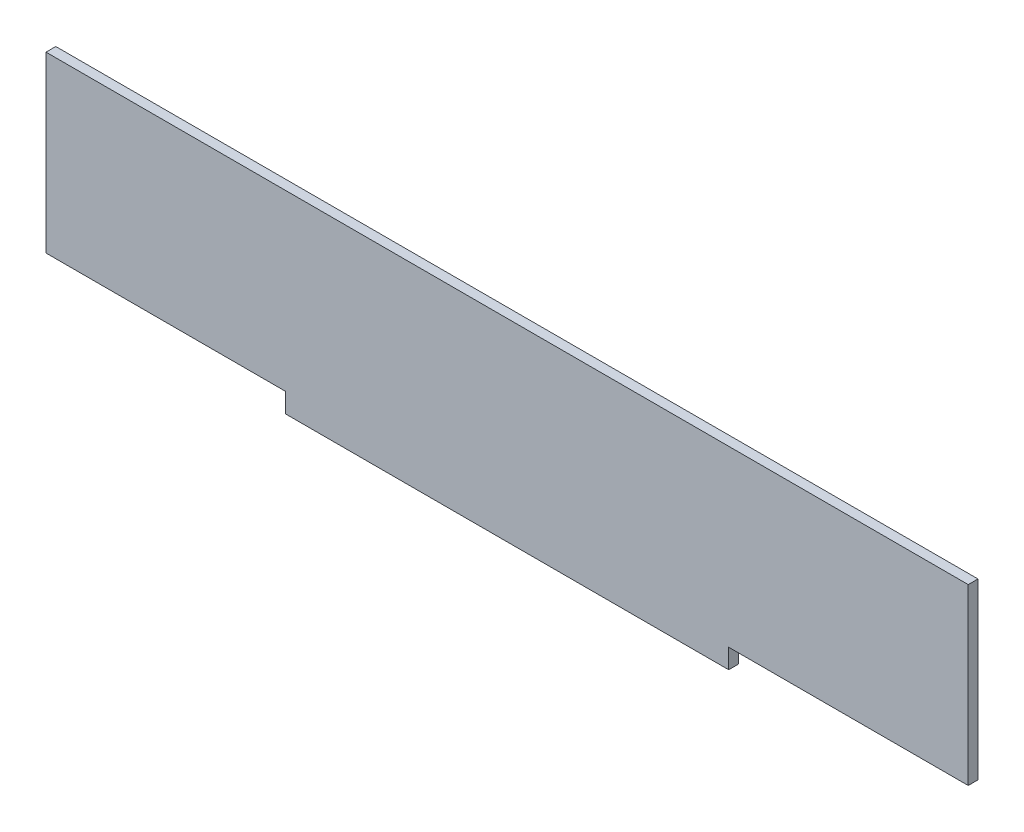
SolidWorks part; units mm, degrees
material "ABS"
ref_plane "X-Y Datum" through (0, 0, 0) normal (0, 0, 1) x (1, 0, 0)
ref_plane "X-Z Datum" through (0, 0, 0) normal (0, 1, 0) x (1, 0, 0)
ref_plane "Y-Z Datum" through (0, 0, 0) normal (1, 0, 0) x (0, 0, -1)
sketch "Sketch1" plane through (0, 0, 0) normal (0, 0, 1) x (1, 0, 0)
  line L1 (-149.85, 28.275) -> (149.85, 28.275)
  line L2 (-149.85, 28.275) -> (-149.85, -28.275)
  line L3 (-149.85, -28.275) -> (149.85, -28.275)
  line L4 (149.85, 28.275) -> (149.85, -28.275)
  line L5 (-149.85, 28.275) -> (149.85, -28.275) construction
  line L6 (-149.85, -28.275) -> (149.85, 28.275) construction
  point P0 (0, 0)
  dimension "D1" = 56.55
  dimension "D2" = 299.7
extrude "Boss-Extrude1" add sketch "Sketch1" along normal blind 3.175
sketch "Sketch2" plane through (0, -28.275, 0) normal (0, -1, 0) x (1, 0, 0)
  line L0 (0, 0) -> (0, 3.175) construction
  line L1 (-149.85, 3.175) -> (149.85, 3.175) construction
  line L2 (-149.85, 0) -> (149.85, 0) construction
  line L3 (-72, 3.175) -> (72, 3.175)
  line L4 (-72, 3.175) -> (-72, 0)
  line L5 (-72, 0) -> (72, 0)
  line L6 (72, 3.175) -> (72, 0)
  line L7 (-72, 3.175) -> (72, 0) construction
  line L8 (-72, 0) -> (72, 3.175) construction
  point P5 (0, 1.5875)
  dimension "D1" = 144
extrude "Boss-Extrude2" add sketch "Sketch2" along normal blind 6.35
